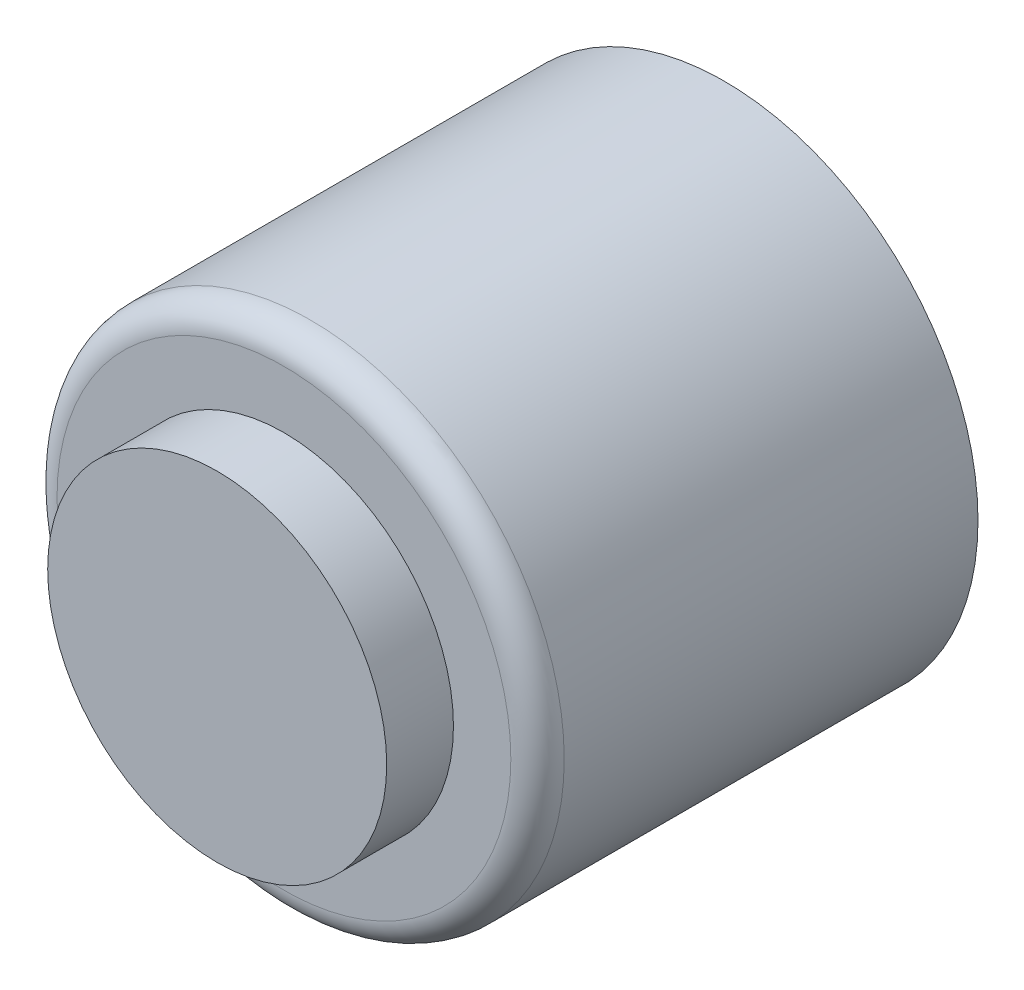
SolidWorks part; units mm, degrees
material "Acrylic (Medium-high impact)"
ref_plane "Front Plane" through (0, 0, 0) normal (0, 0, 1) x (1, 0, 0)
ref_plane "Top Plane" through (0, 0, 0) normal (0, 1, 0) x (1, 0, 0)
ref_plane "Right Plane" through (0, 0, 0) normal (1, 0, 0) x (0, 0, -1)
sketch "Sketch1" plane through (0, 0, 0) normal (1, 0, 0) x (0, 0, -1)
  line L0 (0, 0) -> (0, -12.7)
  line L1 (0, -12.7) -> (5, -12.7)
  line L2 (5, -12.7) -> (5, -19)
  line L3 (5, -19) -> (38, -19)
  line L4 (38, -19) -> (38, -18)
  line L5 (38, -18) -> (34.5174, -14.5174)
  line L6 (0, 0) -> (6, 0)
  line L7 (6, 0) -> (38, 0)
  arc A0 (34.5174, -14.5174) -> (38, 0) centre (6, 0) ccw
  dimension "D7" = 32
  dimension "D1" = 12.7
  dimension "D2" = 135
  dimension "D3" = 19
  dimension "D4" = 5
  dimension "D5" = 1
  dimension "D6" = 38
revolve "Revolve1" add sketch "Sketch1" angle 360 about L6
fillet "Fillet1" radius 2 1 edges at (19, 0, -5)
